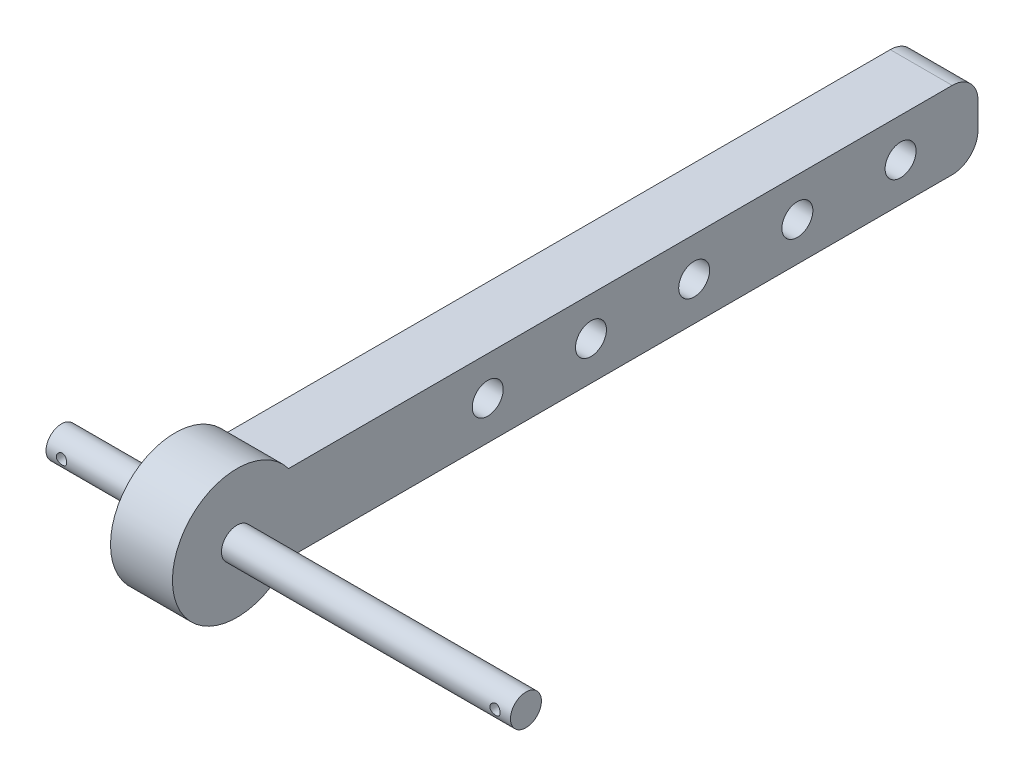
SolidWorks part; units mm, degrees
ref_plane "前视基准面" through (0, 0, 0) normal (0, 0, 1) x (1, 0, 0)
ref_plane "上视基准面" through (0, 0, 0) normal (0, 1, 0) x (1, 0, 0)
ref_plane "右视基准面" through (0, 0, 0) normal (1, 0, 0) x (0, 0, -1)
other "Configuration Table"
sketch "草图1" plane through (0, 0, 0) normal (1, 0, 0) x (0, 0, -1)
  line L1 (0, 0) -> (150, 0)
  line L2 (0, 0) -> (0, 15)
  line L3 (0, 15) -> (150, 15)
  line L4 (150, 0) -> (150, 15)
  dimension "D1" = 15
  dimension "D2" = 150
extrude "凸台-拉伸1" add sketch "草图1" along normal blind 12
fillet "圆角1" radius 5 4 edges at (6, 0, -150) (6, 15, -150) (6, 0, 0) (6, 15, 0)
sketch "草图6" plane through (12, 0, 0) normal (1, 0, 0) x (0, 0, -1)
  circle A0 centre (6.4, 7.5) radius 12.5
extrude "凸台-拉伸2" add sketch "草图6" against normal up to surface (12 mm away) up to face at (0, 7.5, -75)
sketch "草图15" plane through (0, 0, 0) normal (-1, 0, 0) x (0, 0, 1)
  circle A2 centre (-6.4, 7.5) radius 3
  dimension "D1" = 6
extrude "凸台-拉伸5" add sketch "草图15" along normal blind 22 and the other way blind 68
sketch "草图16" plane through (0, 0, 0) normal (0, 0, 1) x (1, 0, 0)
  line L0 (-22, 7.5) -> (-24.7951, 7.5) construction
  line L1 (-22, 10.5) -> (-22, 4.5) construction
  line L2 (68, 7.5) -> (28.4852, 7.5) construction
  line L3 (68, 4.5) -> (68, 10.5) construction
  circle A0 centre (-19, 7.5) radius 1
  circle A1 centre (65, 7.5) radius 1
  dimension "D2" = 2
  dimension "D3" = 2
  dimension "D1" = 3
  dimension "D4" = 3
extrude "切除-拉伸9" cut sketch "草图16" against normal up to next
sketch "草图17" plane through (0, 0, 0) normal (-1, 0, 0) x (0, 0, 1)
  line L0 (-150, 7.5) -> (-31.7081, 7.5) construction
  line L1 (-150, 5) -> (-150, 10) construction
  circle A0 centre (-135, 7.5) radius 3
  circle A1 centre (-115, 7.5) radius 3
  circle A2 centre (-95, 7.5) radius 3
  circle A3 centre (-75, 7.5) radius 3
  circle A4 centre (-55, 7.5) radius 3
  dimension "D6" = 6
  dimension "D7" = 6
  dimension "D8" = 6
  dimension "D9" = 6
  dimension "D10" = 6
  dimension "D1" = 15
  dimension "D2" = 20
  dimension "D3" = 20
  dimension "D4" = 20
  dimension "D5" = 20
extrude "切除-拉伸10" cut sketch "草图17" against normal up to next
